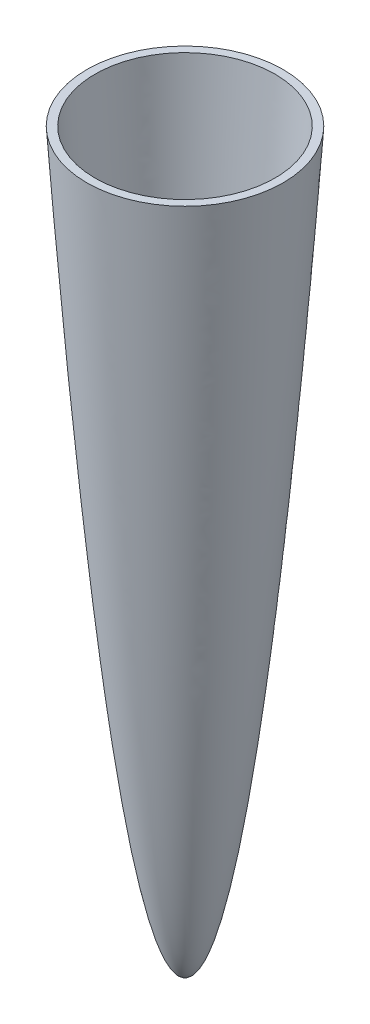
SolidWorks part; units mm, degrees
ref_plane "Front Plane" through (0, 0, 0) normal (0, 0, 1) x (1, 0, 0)
ref_plane "Top Plane" through (0, 0, 0) normal (0, 1, 0) x (1, 0, 0)
ref_plane "Right Plane" through (0, 0, 0) normal (1, 0, 0) x (0, 0, -1)
sketch "Sketch4" plane through (0, 0, 0) normal (1, 0, 0) x (0, 0, -1)
  line L0 (-10.16, 76.2) -> (-9.3201, 76.2043)
  line L1 (0, 1) -> (0, 0)
  line L2 (0, 0) -> (0, 76.2113) construction
  spline S0 degree 4 poles (0, 0) (-0.0494, 0.0001) (-0.1138, 0.0063) (-0.1954, 0.0248) (-0.299, 0.0642) (-0.3808, 0.1046) (-0.4762, 0.1642) (-0.5884, 0.2514) (-0.72, 0.3765) (-0.8835, 0.5666) (-1.0957, 0.8693) (-1.3876, 1.3888) (-1.81, 2.3474) (-2.4368, 4.2284) (-3.2395, 7.5027) (-4.0858, 12.0721) (-4.9231, 17.677) (-5.6995, 23.8205) (-6.3845, 29.9584) (-7.006, 36.1284) (-7.5751, 42.2621) (-8.1093, 48.469) (-8.5411, 53.7902) (-8.9061, 58.5311) (-9.1815, 62.2028) (-9.428, 65.6159) (-9.6601, 68.8402) (-10.0103, 73.9531) (-10.1932, 76.6783) (-10.4435, 80.503) (-10.5688, 82.4501) (-10.622, 83.2888) (-10.6572, 83.8402) knots 0 0 0 0 0 0.002307 0.003039 0.003912 0.005199 0.006581 0.008316 0.010577 0.013716 0.018335 0.025658 0.038517 0.062864 0.111321 0.183958 0.256595 0.329232 0.401869 0.474507 0.547144 0.619781 0.692418 0.728737 0.765055 0.801374 0.837692 0.910329 0.955165 0.977582 1 1 1 1 1 construction
  spline S1 degree 4 poles (0, 0) (-0.0494, 0.0001) (-0.1138, 0.0063) (-0.1954, 0.0248) (-0.299, 0.0642) (-0.3808, 0.1046) (-0.4762, 0.1642) (-0.5884, 0.2514) (-0.72, 0.3765) (-0.8835, 0.5666) (-1.0957, 0.8693) (-1.3876, 1.3888) (-1.81, 2.3474) (-2.4368, 4.2284) (-3.2395, 7.5027) (-4.0858, 12.0721) (-4.9231, 17.677) (-5.6995, 23.8205) (-6.3845, 29.9584) (-7.006, 36.1284) (-7.5751, 42.2621) (-8.1093, 48.469) (-8.5411, 53.7902) (-8.9061, 58.5311) (-9.1815, 62.2028) (-9.428, 65.6159) (-9.6601, 68.8402) (-9.9277, 72.7473) (-10.0664, 74.7954) (-10.16, 76.2) knots 0 0 0 0 0 0.002307 0.003039 0.003912 0.005199 0.006581 0.008316 0.010577 0.013716 0.018335 0.025658 0.038517 0.062864 0.111321 0.183958 0.256595 0.329232 0.401869 0.474507 0.547144 0.619781 0.692418 0.728737 0.765055 0.801374 0.837692 0.910329 0.910329 0.910329 0.910329 0.910329
  spline S2 degree 4 poles (0, 1) (-0.0432, 0.9999) (-0.1004, 1.0057) (-0.1726, 1.0238) (-0.2624, 1.0616) (-0.3324, 1.0998) (-0.4125, 1.1546) (-0.5066, 1.2341) (-0.6188, 1.3493) (-0.7606, 1.5275) (-0.9493, 1.8184) (-1.2186, 2.3409) (-1.6219, 3.3486) (-2.2359, 5.4169) (-2.975, 8.8427) (-3.7493, 13.523) (-4.5087, 19.1376) (-5.2053, 25.1472) (-5.8231, 31.1106) (-6.3919, 37.1648) (-6.9099, 43.0845) (-7.409, 49.2331) (-7.8567, 55.0126) (-8.3207, 61.4053) (-8.6997, 66.7888) (-9.125, 73.1789) (-9.3647, 76.8792) (-9.5721, 80.1608) (-9.7276, 82.6349) (-9.7501, 83.0209) (-9.7995, 83.8085) knots 0 0 0 0 0 0.002045 0.002744 0.003528 0.00464 0.005839 0.007369 0.009393 0.012302 0.016675 0.0239 0.037364 0.064065 0.119352 0.191239 0.263126 0.335013 0.406901 0.478788 0.550675 0.622562 0.694449 0.766337 0.838224 0.910111 0.955055 0.977528 1 1 1 1 1 construction
  spline S3 degree 4 poles (0, 1) (-0.0432, 0.9999) (-0.1004, 1.0057) (-0.1726, 1.0238) (-0.2624, 1.0616) (-0.3324, 1.0998) (-0.4125, 1.1546) (-0.5066, 1.2341) (-0.6188, 1.3493) (-0.7606, 1.5275) (-0.9493, 1.8184) (-1.2186, 2.3409) (-1.6219, 3.3486) (-2.2359, 5.4169) (-2.975, 8.8427) (-3.7493, 13.523) (-4.5087, 19.1376) (-5.2053, 25.1472) (-5.8231, 31.1106) (-6.3919, 37.1648) (-6.9099, 43.0845) (-7.409, 49.2331) (-7.8567, 55.0126) (-8.3207, 61.4053) (-8.6997, 66.7888) (-9.0517, 72.0769) (-9.2319, 74.8356) (-9.3201, 76.2043) knots 0 0 0 0 0 0.002045 0.002744 0.003528 0.00464 0.005839 0.007369 0.009393 0.012302 0.016675 0.0239 0.037364 0.064065 0.119352 0.191239 0.263126 0.335013 0.406901 0.478788 0.550675 0.622562 0.694449 0.766337 0.838224 0.910111 0.910111 0.910111 0.910111 0.910111
revolve "Revolve2" add sketch "Sketch4" angle 360 about L2
